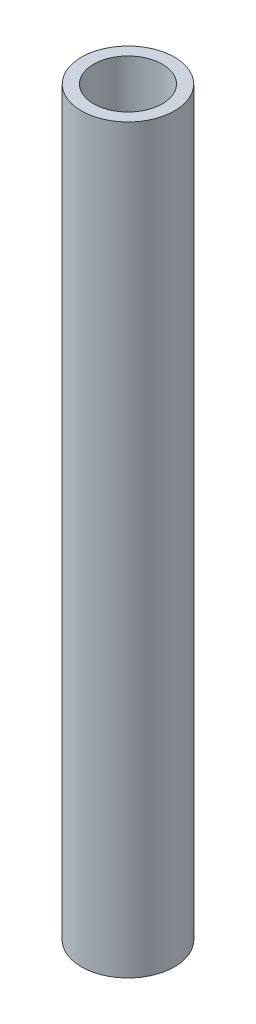
SolidWorks part; units mm, degrees
ref_plane "Front" through (0, 0, 0) normal (0, 0, 1) x (1, 0, 0)
ref_plane "Top" through (0, 0, 0) normal (0, 1, 0) x (1, 0, 0)
ref_plane "Right" through (0, 0, 0) normal (1, 0, 0) x (0, 0, -1)
sketch "Sketch1" plane through (0, 0, 0) normal (0, 1, 0) x (1, 0, 0)
  circle A0 centre (0, 0) radius 3.5052
  circle A1 centre (0, 0) radius 4.7498
extrude "Boss-Extrude1" add sketch "Sketch1" along normal blind 75.6412
